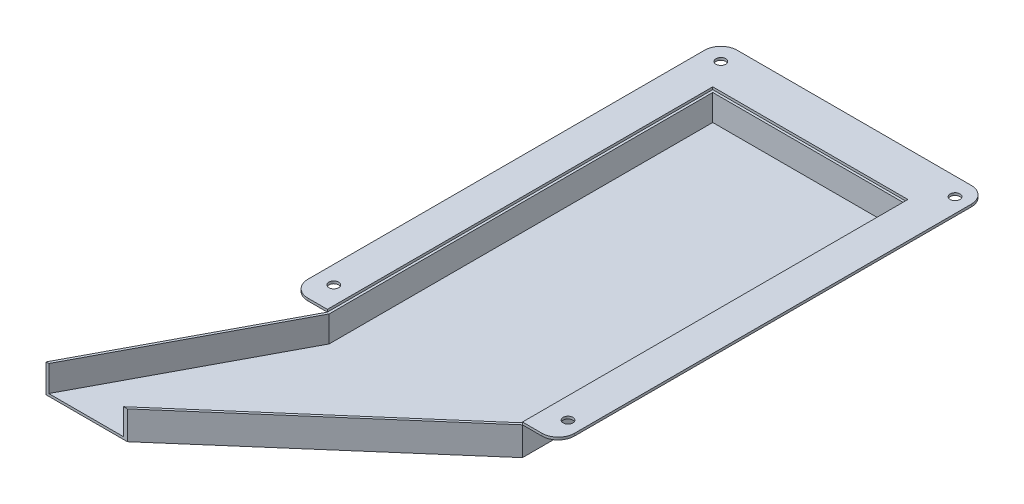
SolidWorks part; units mm, degrees
ref_plane "Front Plane" through (0, 0, 0) normal (0, 0, 1) x (1, 0, 0)
ref_plane "Top Plane" through (0, 0, 0) normal (0, 1, 0) x (1, 0, 0)
ref_plane "Right Plane" through (0, 0, 0) normal (1, 0, 0) x (0, 0, -1)
sketch "Sketch1" plane through (0, 0, 0) normal (0, 1, 0) x (1, 0, 0)
  line L0 (0, 0) -> (0, 237)
  line L1 (0, 237) -> (120, 237)
  line L2 (120, 237) -> (120, 0)
  line L3 (120, 0) -> (-10, -113)
  line L4 (-10, -113) -> (-60, -113)
  line L5 (-60, -113) -> (0, 0)
  dimension "D1" = 237
  dimension "D2" = 237
  dimension "D3" = 120
  dimension "D4" = 50
  dimension "D5" = 350
  dimension "D6" = 130
extrude "Boss-Extrude1" add sketch "Sketch1" along normal blind 1.5
sketch "Sketch2" plane through (0, 1.5, 0) normal (0, 1, 0) x (1, 0, 0)
  line L0 (0, 237) -> (120, 237)
  line L1 (120, 237) -> (120, 0)
  line L2 (-10, -113) -> (120, 0) construction
  line L3 (120, 0) -> (120, 237) construction
  line L4 (120, 0) -> (-10, -113)
  line L6 (-60, -113) -> (0, 0)
  line L7 (0, 0) -> (0, 237)
  line L8 (1.5, -0.3735) -> (1.5, 235.5)
  line L9 (1.5, 235.5) -> (118.5, 235.5)
  line L10 (118.5, 235.5) -> (118.5, 0.6836)
  line L11 (118.5, 0.6836) -> (-10.5608, -111.5)
  line L13 (-57.5052, -111.5) -> (1.5, -0.3735)
  line L14 (-10.5608, -111.5) -> (-57.5052, -111.5) construction
  line L15 (-10, -113) -> (-60, -113) construction
  line L16 (-57.5052, -111.5) -> (-58.3017, -113)
  line L17 (-60, -113) -> (-58.3017, -113)
  line L18 (-60, -113) -> (-10, -113) construction
  line L19 (-10.5608, -111.5) -> (-12.2865, -113)
  line L21 (-12.2865, -113) -> (-10, -113)
  dimension "D1" = 1.5
extrude "Boss-Extrude2" add sketch "Sketch2" along normal blind 16
sketch "Sketch3" plane through (0, 17.5, 0) normal (0, 1, 0) x (1, 0, 0)
  line L0 (-22, 264) -> (142, 264)
  line L1 (142, 264) -> (142, 0)
  line L2 (-22, 264) -> (-22, 0)
  line L3 (-22, 0) -> (0, 0)
  line L4 (142, 0) -> (120, 0)
  line L5 (120, 0) -> (120, 237)
  line L6 (120, 237) -> (0, 237)
  line L7 (0, 237) -> (0, 0)
  circle A0 centre (-11, 253) radius 3
  circle A1 centre (133, 253) radius 3
  circle A2 centre (-11, 15) radius 3
  circle A3 centre (133, 15) radius 3
  dimension "D4" = 6
  dimension "D7" = 6
  dimension "D11" = 6
  dimension "D12" = 6
  dimension "D1" = 27
  dimension "D2" = 22
  dimension "D3" = 22
  dimension "D5" = 11
  dimension "D6" = 11
  dimension "D8" = 11
  dimension "D9" = 144
  dimension "D10" = 11
  dimension "D13" = 144
  dimension "D14" = 238
  dimension "D15" = 238
extrude "Boss-Extrude3" add sketch "Sketch3" along normal blind 1.5 separate body
fillet "Fillet1" radius 10 4 edges at (-22, 18.25, -264) (142, 18.25, -264) (142, 18.25, 0) (-22, 18.25, 0)
